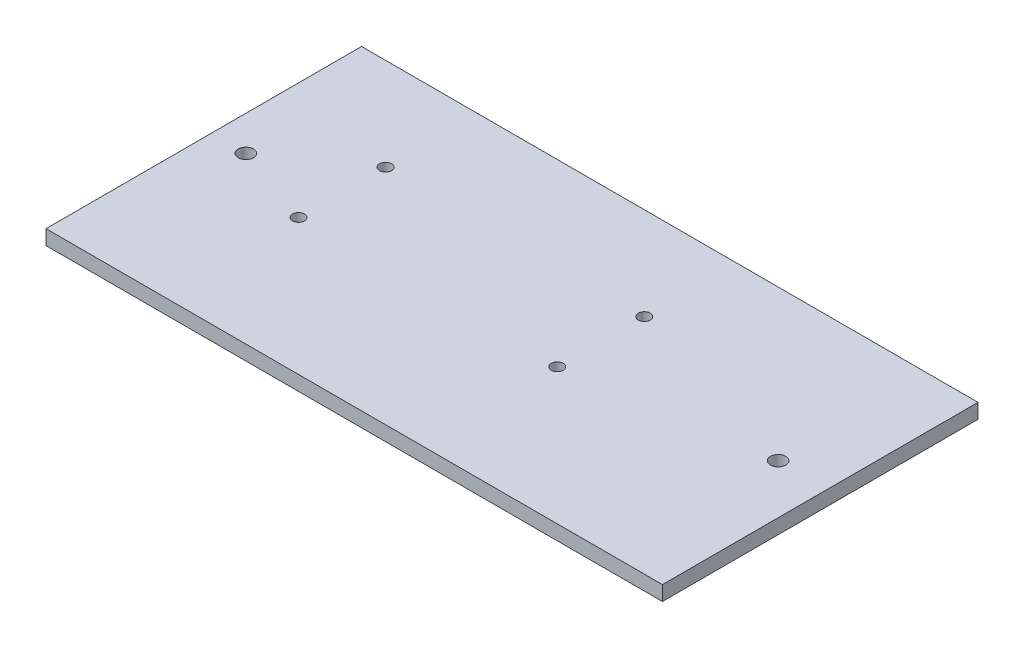
SolidWorks part; units mm, degrees
ref_plane "Front Plane" through (0, 0, 0) normal (0, 0, 1) x (1, 0, 0)
ref_plane "Top Plane" through (0, 0, 0) normal (0, 1, 0) x (1, 0, 0)
ref_plane "Right Plane" through (0, 0, 0) normal (1, 0, 0) x (0, 0, -1)
sketch "Sketch1" plane through (0, 0, 0) normal (0, 1, 0) x (1, 0, 0)
  line L0 (0, 34.0875) -> (0, -34.0875) construction
  line L1 (-66.5875, 34.0875) -> (66.5875, 34.0875)
  line L2 (-66.5875, 34.0875) -> (-66.5875, -34.0875)
  line L3 (-66.5875, -34.0875) -> (66.5875, -34.0875)
  line L4 (66.5875, 34.0875) -> (66.5875, -34.0875)
  line L5 (-66.5875, 34.0875) -> (66.5875, -34.0875) construction
  line L6 (-66.5875, -34.0875) -> (66.5875, 34.0875) construction
  line L7 (-59.0875, 26.5875) -> (55.9125, 26.5875) construction
  line L8 (-59.0875, 26.5875) -> (-59.0875, -23.4125) construction
  line L9 (-59.0875, -23.4125) -> (55.9125, -23.4125) construction
  line L10 (55.9125, 26.5875) -> (55.9125, -23.4125) construction
  line L11 (-66.5875, 0) -> (66.5875, 0) construction
  circle A1 centre (-59.0875, 1.5875) radius 1.65
  circle A2 centre (55.9125, 1.5875) radius 1.65
  point P0 (0, 0)
  point P6 (0, 0)
  dimension "D1" = 133.175
  dimension "D2" = 7.5
  dimension "D3" = 7.5
  dimension "D4" = 10.675
  dimension "D5" = 10.675
  dimension "D6" = 68.175
extrude "Boss-Extrude1" add sketch "Sketch1" along normal blind 3.175
sketch "Sketch2" plane through (0, 3.175, 0) normal (0, 1, 0) x (1, 0, 0)
  line L0 (66.5875, 34.0875) -> (-66.5875, 34.0875) construction
  line L1 (14.4875, -4.7125) -> (-41.4125, -4.7125) construction
  line L2 (14.4875, -4.7125) -> (14.4875, 14.0875) construction
  line L3 (14.4875, 14.0875) -> (-41.4125, 14.0875) construction
  line L4 (-41.4125, -4.7125) -> (-41.4125, 14.0875) construction
  line L5 (14.4875, -4.7125) -> (-41.4125, 14.0875) construction
  line L6 (14.4875, 14.0875) -> (-41.4125, -4.7125) construction
  line L7 (-66.5875, 34.0875) -> (-66.5875, -34.0875) construction
  circle A0 centre (14.4875, -4.7125) radius 1.3
  circle A1 centre (-41.4125, -4.7125) radius 1.3
  circle A2 centre (-41.4125, 14.0875) radius 1.3
  circle A3 centre (14.4875, 14.0875) radius 1.3
  point P0 (-13.4625, 4.6875)
  dimension "D3" = 2.6
  dimension "D1" = 55.9
  dimension "D2" = 18.8
  dimension "D4" = 20
  dimension "D5" = 25.175
extrude "Cut-Extrude1" cut sketch "Sketch2" against normal up to surface (3.175 mm away) up to face at (0, 0, 0)
